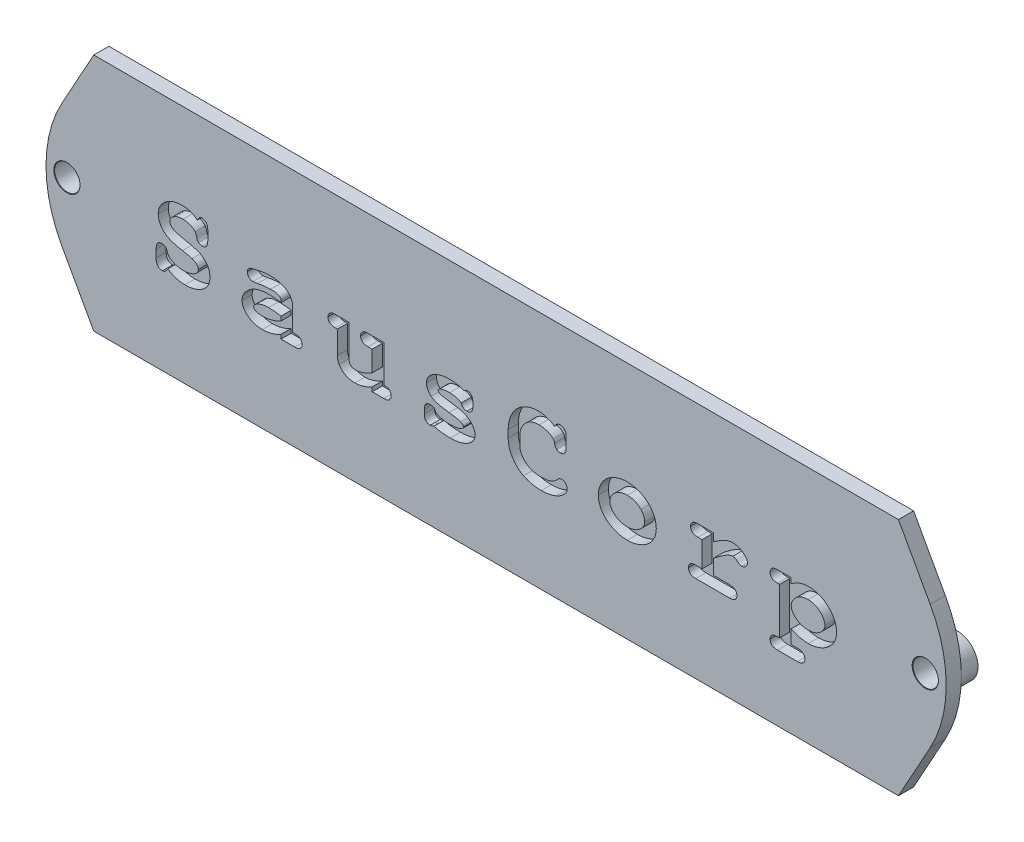
SolidWorks part; units mm, degrees
ref_plane "Front Plane" through (0, 0, 0) normal (0, 0, 1) x (1, 0, 0)
ref_plane "Top Plane" through (0, 0, 0) normal (0, 1, 0) x (1, 0, 0)
ref_plane "Right Plane" through (0, 0, 0) normal (1, 0, 0) x (0, 0, -1)
sketch "Sketch1" plane through (0, 0, 0) normal (0, 0, 1) x (1, 0, 0)
  line L10 (-50.6, 15.04) -> (50.6, 15.04)
  line L11 (50.6, 15.04) -> (54.5903, 7.8135)
  line L12 (54.5903, -7.8135) -> (50.6, -15.04)
  line L13 (50.6, -15.04) -> (-50.6, -15.04)
  line L14 (-50.6, -15.04) -> (-54.5903, -7.8135)
  line L15 (-54.5903, 7.8135) -> (-50.6, 15.04)
  line L16 (-50.6, 15.04) -> (-50.6, -15.04) construction
  line L18 (50.6, 15.04) -> (50.6, -15.04) construction
  arc A4 (54.5903, 7.8135) -> (54.5903, -7.8135) centre (40.44, 0) cw
  arc A5 (-54.5903, -7.8135) -> (-54.5903, 7.8135) centre (-40.44, 0) cw
  point P5 (0, 15.04)
  dimension "D1" = 10.16
  dimension "D3" = 8.255
  dimension "D4" = 101.2
  dimension "D5" = 30.08
extrude "Boss-Extrude1" add sketch "Sketch1" along normal blind 1.905
sketch "Sketch6" plane through (0, 0, 0) normal (0, 0, -1) x (-1, 0, 0)
  circle A0 centre (-53.975, 0) radius 2.6292
  circle A1 centre (53.975, 0) radius 2.6292
  arc A2 (-54.5903, 7.8135) -> (-54.5903, -7.8135) centre (-40.44, 0) ccw construction
  arc A3 (54.5903, -7.8135) -> (54.5903, 7.8135) centre (40.44, 0) ccw construction
  point P10 (-53.975, 0)
  dimension "D1" = 107.95
extrude "Boss-Extrude4" add sketch "Sketch6" along normal offset from surface (2.095 mm away) 4 up to face at (0, 0, 1.905)
sketch "Sketch2" plane through (0, 0, 1.905) normal (0, 0, 1) x (1, 0, 0)
  line L0 (-53.975, 0) -> (53.975, 0) construction
  point P3 (0, 0)
  point P5 (-53.975, 0)
  point P6 (53.975, 0)
  dimension "D1" = 107.95
hole_wizard "Ø3.0mm Dowel Hole1" positions "Sketch2" profile "Sketch3" hole size "Ø3.0" standard "ANSI Metric" end condition through all
sketch "Sketch3" plane through (53.975, 0, 1.905) normal (1, 0, 0) x (0, -1, 0)
  line L0 (0, 0) -> (0, 4)
  line L1 (0, 4) -> (1.6, 4)
  line L2 (1.6, 4) -> (1.6, 0.05)
  line L3 (1.6, 0.05) -> (1.65, 0)
  line L5 (1.65, 0) -> (0, 0)
  line L6 (-1.6, 0.05) -> (-1.65, 0) construction
  line L11 (0, -6.35) -> (0, 107.95) construction
  dimension "Thru Hole Dia." = 3.2
  dimension "Thru Hole Depth" = 4
  dimension "Near C'Sink Dia." = 3.3
  dimension "Near C'Sink Angle" = 90
sketch "Sketch4" plane through (0, 0, 1.905) normal (0, 0, 1) x (1, 0, 0)
  line L0 (0, -12.5998) -> (0, 12.5998) construction
  line L1 (-50.8, 12.5998) -> (50.8, 12.5998) construction
  line L2 (-50.8, 12.5998) -> (-50.8, -12.5998) construction
  line L3 (-50.8, -12.5998) -> (50.8, -12.5998) construction
  line L4 (50.8, 12.5998) -> (50.8, -12.5998) construction
  line L5 (-43.815, -4.1275) -> (43.815, -4.1275) construction
  line L6 (-43.815, -4.1275) -> (-43.815, 4.1275) construction
  line L7 (-43.815, 4.1275) -> (43.815, 4.1275) construction
  line L8 (43.815, -4.1275) -> (43.815, 4.1275) construction
  line L9 (-50.8, 0) -> (50.8, 0) construction
  text T0 "SausCorp" font "Courier New" height in points 32
  point P4 (-50.8, 0)
  point P6 (0, 12.5998)
  point P15 (-43.815, 0)
  point P16 (0, -4.1275)
  dimension "D1" = 101.6
  dimension "D2" = 25.1995
  dimension "D3" = 87.63
  dimension "D4" = 8.255
extrude "Cut-Extrude1" cut sketch "Sketch4" against normal blind 1.27
